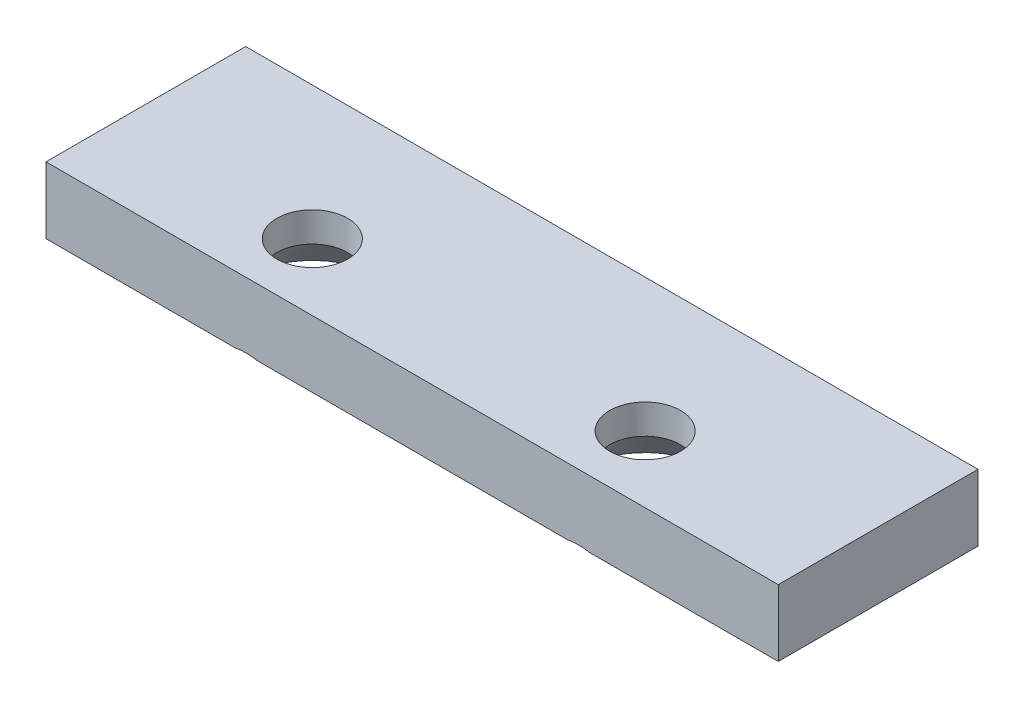
SolidWorks part; units mm, degrees
material "6061 Alloy"
ref_plane "Front Plane" through (0, 0, 0) normal (0, 0, 1) x (1, 0, 0)
ref_plane "Top Plane" through (0, 0, 0) normal (0, 1, 0) x (1, 0, 0)
ref_plane "Right Plane" through (0, 0, 0) normal (1, 0, 0) x (0, 0, -1)
sketch "Sketch1" plane through (0, 0, 0) normal (0, 1, 0) x (1, 0, 0)
  line L1 (34.925, -9.525) -> (-34.925, -9.525)
  line L2 (34.925, -9.525) -> (34.925, 9.525)
  line L3 (34.925, 9.525) -> (-34.925, 9.525)
  line L4 (-34.925, -9.525) -> (-34.925, 9.525)
  line L5 (34.925, -9.525) -> (-34.925, 9.525) construction
  line L6 (34.925, 9.525) -> (-34.925, -9.525) construction
  point P0 (0, 0)
  dimension "D1" = 69.85
  dimension "D2" = 19.05
extrude "Boss-Extrude1" add sketch "Sketch1" along normal blind 6.35
hole_wizard "CSK for 1/4 Flat Head Machine Screw1" positions "Sketch2" profile "Sketch3" countersink size "1/4" standard "ANSI Inch"
sketch "Sketch2" plane through (0, 0, 0) normal (0, -1, 0) x (-1, 0, 0)
  line L0 (34.925, -9.525) -> (-34.925, -9.525) construction
  line L1 (34.925, 9.525) -> (34.925, -9.525) construction
  line L2 (-34.925, -9.525) -> (-34.925, 9.525) construction
  point P0 (15.875, -3.175)
  point P2 (-15.875, -3.175)
  dimension "D1" = 6.35
  dimension "D2" = 6.35
  dimension "D3" = 19.05
  dimension "D4" = 19.05
sketch "Sketch3" plane through (-15.875, 0, 3.175) normal (1, 0, 0) x (0, 0, -1)
  line L0 (0, 0) -> (0, 17.2698)
  line L1 (0, 17.2698) -> (3.3782, 15.24)
  line L2 (3.3782, 15.24) -> (3.3782, 3.5209)
  line L3 (3.3782, 3.5209) -> (6.4389, 0)
  line L5 (6.4389, 0) -> (0, 0)
  line L6 (-3.3782, 3.5209) -> (-6.4389, 0) construction
  line L10 (0, 17.2698) -> (-3.3782, 15.24) construction
  line L11 (0, -6.35) -> (0, 107.95) construction
  dimension "Hole Dia." = 6.7564
  dimension "Hole Depth" = 15.24
  dimension "Near C'Sink Dia." = 12.8778
  dimension "Near C'Sink Angle" = 82
  dimension "Drill Angle" = 118
